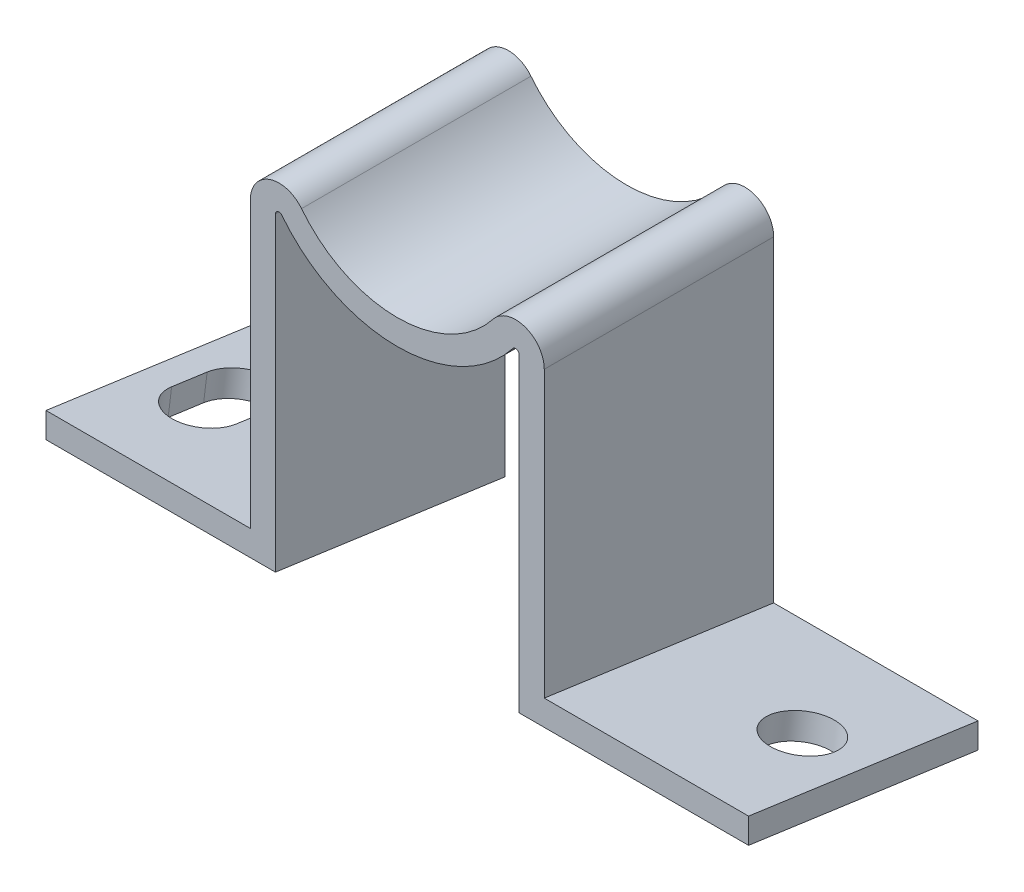
SolidWorks part; units mm, degrees
material "AISI 1010 钢，热轧条材"
ref_plane "前视基准面" through (0, 0, 0) normal (0, 0, 1) x (1, 0, 0)
ref_plane "上视基准面" through (0, 0, 0) normal (0, 1, 0) x (1, 0, 0)
ref_plane "右视基准面" through (0, 0, 0) normal (1, 0, 0) x (0, 0, -1)
sketch "草图1" plane through (0, 0, 0) normal (0, 0, 1) x (1, 0, 0)
  line L0 (-17, -12.9904) -> (-17, -66.8639)
  line L1 (-20.5, -12.9904) -> (-20.5, -66.8639)
  line L2 (-17, -66.8639) -> (-20.5, -66.8639)
  line L3 (0, 7.4816) -> (0, 50007.4816) construction
  line L4 (17, -66.8639) -> (20.5, -66.8639)
  line L5 (20.5, -12.9904) -> (20.5, -66.8639)
  line L6 (17, -12.9904) -> (17, -66.8639)
  arc A0 (-13.3571, -10.516) -> (13.3571, -10.516) centre (0, 0) ccw
  arc A1 (-16.1071, -12.6811) -> (16.1071, -12.6811) centre (0, 0) ccw
  arc A2 (-13.3571, -10.516) -> (-20.5, -12.9904) centre (-16.5, -12.9904) ccw
  circle A3 centre (0, 0) radius 17 construction
  circle A4 centre (0, 0) radius 20.5 construction
  arc A5 (-16.1071, -12.6811) -> (-17, -12.9904) centre (-16.5, -12.9904) ccw
  arc A6 (16.1071, -12.6811) -> (17, -12.9904) centre (16.5, -12.9904) cw
  arc A7 (13.3571, -10.516) -> (20.5, -12.9904) centre (16.5, -12.9904) cw
  point P1 (20.5, 0)
  point P4 (16.2572, 4.9703)
  point P15 (20.5, 0)
  point P18 (16.2572, 4.9703)
  dimension "D1" = 3.5
  dimension "D2" = 4
  dimension "D3" = 17
  dimension "D4" = 3.5
extrude "凸台-拉伸1" add sketch "草图1" along normal mid plane 32
sketch "草图2" plane through (0, 0, 0) normal (1, 0, 0) x (0, 0, -1)
  line L0 (0, 0) -> (50000, 0) construction
  line L1 (0, 0) -> (0, -50000) construction
  line L2 (29.9617, -62.7108) -> (0, -58.5) construction
  line L3 (16, -60.7487) -> (-16, -56.2513)
  line L4 (16, -66.8639) -> (16, -12.9904) construction
  line L5 (-16, -66.8639) -> (-16, -12.9904) construction
  line L6 (-16, -56.2513) -> (-16, -66.8639)
  line L7 (-16, -66.8639) -> (16, -66.8639)
  line L8 (16, -66.8639) -> (16, -60.7487)
  dimension "D1" = 8
  dimension "D2" = 58.5
extrude "切除-拉伸1" cut sketch "草图2" against normal mid plane 100
sketch "草图3" plane through (-20.5, 0, 0) normal (-1, 0, 0) x (0, 0, 1)
  line L0 (-16, -60.7487) -> (16, -56.2513)
  line L1 (-16, -57.2143) -> (16, -52.717)
  line L2 (16, -12.9904) -> (16, -56.2513) construction
  line L4 (-16, -60.7487) -> (-16, -57.2143)
  line L5 (16, -56.2513) -> (16, -52.717)
  line L7 (-16.4871, -57.2827) -> (15.5129, -52.7854) construction
  dimension "D1" = 3.5
extrude "凸台-拉伸2" add sketch "草图3" along normal blind 28.5
mirror "镜向1" about plane through (0, 0, 0) normal (1, 0, 0) of "凸台-拉伸2"
sketch "草图4" plane through (0, -53.901, 7.5753) normal (0, 0.9903, -0.1392) x (1, 0, 0)
  line L0 (0, 0) -> (0, -50000) construction
  line L1 (-49, 7.6497) -> (49, 7.6497) construction
  line L2 (-49, -8.5075) -> (-49, 23.807) construction
  line L3 (49, -8.5075) -> (49, 23.807) construction
  line L4 (-40.5, 23.807) -> (-40.5, -8.5075) construction
  line L5 (-49, 23.807) -> (-20.5, 23.807) construction
  line L6 (-49, -8.5075) -> (-20.5, -8.5075) construction
  line L7 (40.5, 23.807) -> (40.5, -8.5075) construction
  line L8 (-36, 10.1497) -> (-36, 5.1497)
  line L9 (-45, 10.1497) -> (-45, 5.1497)
  arc A0 (-36, 10.1497) -> (-45, 10.1497) centre (-40.5, 10.1497) ccw
  arc A1 (-45, 5.1497) -> (-36, 5.1497) centre (-40.5, 5.1497) ccw
  circle A2 centre (40.5, 7.6497) radius 4.5
  dimension "D2" = 9
  dimension "D4" = 9
  dimension "D1" = 81
  dimension "D3" = 5
extrude "切除-拉伸2" cut sketch "草图4" against normal blind 28.5
